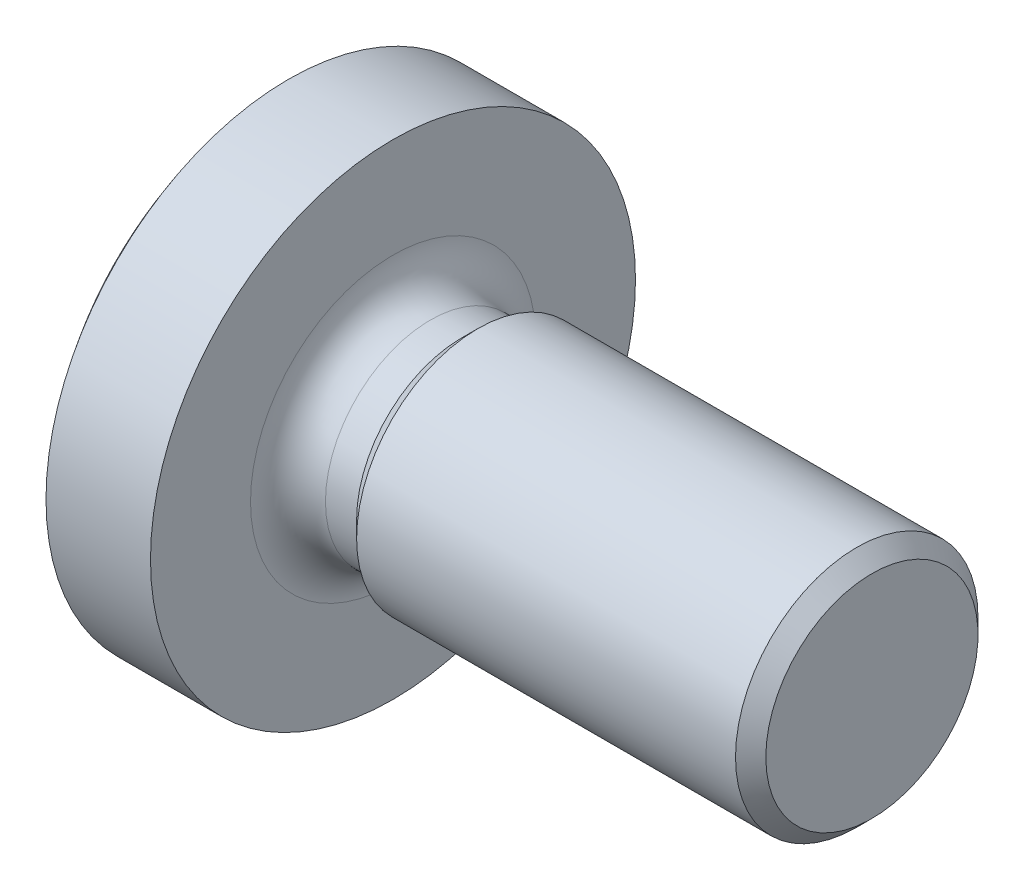
SolidWorks part; units mm, degrees
revolve "基体-旋转" add sketch "草图2" angle 360 about L0
sketch "草图2" plane through (0, 0, 0) normal (0, 0, 1) x (1, 0, 0)
  line L0 (-1.3318, 0) -> (6.5885, 0) construction
  line L1 (0, 0) -> (17.1, 0)
  line L2 (17.1, 0) -> (17.1, 2)
  line L3 (17.1, 2) -> (4.5, 2)
  line L4 (4.5, 2) -> (4.232, 1.732)
  line L5 (4.232, 1.732) -> (3.718, 1.732)
  line L6 (3.1, 2.35) -> (3.1, 4)
  line L7 (3.1, 4) -> (1.3765, 4)
  arc A0 (3.1, 2.35) -> (3.718, 1.732) centre (3.718, 2.35) ccw
  arc A1 (0, 0) -> (1.3765, 4) centre (6.5, 0) cw
  dimension "D3" = 6.5
  dimension "dk" = 8
  dimension "d" = 4
  dimension "l" = 14
  dimension "a" = 1.4
  dimension "D1" = 45
  dimension "D2" = 3.464
  dimension "da" = 4.7
  dimension "k" = 3.1
cosmetic thread "装饰螺纹线1" parameters "D1"=12.6, "D2"=3.464
material "钢"
ref_plane "前视" through (0, 0, 0) normal (0, 0, 1) x (1, 0, 0)
ref_plane "上视" through (0, 0, 0) normal (0, 1, 0) x (1, 0, 0)
ref_plane "右视" through (0, 0, 0) normal (1, 0, 0) x (0, 0, -1)
sketch "尺寸草图" plane through (0, 0, 0) normal (0, 0, 1) x (1, 0, 0)
  line L0 (0, 0) -> (14, 0)
  line L1 (0, 0) -> (0, 8)
  line L2 (14, 0) -> (14, 4.7)
  point P5 (0, 4)
  point P6 (13.3, 0)
  point P7 (1.4, 0)
  point P8 (3.1, 0)
  point P9 (7.5, 0)
  point P10 (4.4, 0)
  point P11 (11.6, 0)
  dimension "dk" = 8
  dimension "d" = 4
  dimension "l" = 14
  dimension "a" = 1.4
  dimension "da" = 4.7
  dimension "k" = 3.1
  dimension "P" = 0.7
  dimension "rf" = 6.5
  dimension "m" = 4.4
  dimension "h" = 2.4
sketch "草图3" plane through (0, 0, 0) normal (0, 0, 1) x (1, 0, 0)
  line L0 (16.7538, 2) -> (17.4538, 2)
  line L1 (17.4538, 2) -> (17.1, 1.3938)
  line L2 (17.1, 1.3938) -> (16.7538, 2)
  line L3 (17.1, 2) -> (4.5, 2) construction
  line L4 (17.1, -2) -> (17.1, 2) construction
  line L5 (-0.2428, 0) -> (7.1644, 0) construction
  line L6 (-1.3318, 0) -> (6.5885, 0) construction
  dimension "P" = 0.7
  dimension "D1" = 0.6062
  dimension "D2" = 60
revolve "切除-旋转1" cut sketch "草图3" angle 360 about L5
sketch "草图5" plane through (0, 0, 0) normal (1, 0, 0) x (0, 0, -1)
  line L1 (0.35, 2.2) -> (-0.35, 2.2)
  line L2 (0.35, 2.2) -> (0.35, -2.2)
  line L3 (0.35, -2.2) -> (-0.35, -2.2)
  line L4 (-0.35, 2.2) -> (-0.35, -2.2)
  point P4 (0.35, 0)
  point P5 (0, 2.2)
  dimension "m" = 4.4
  dimension "D1" = 0.7
ref_plane "基准面1" through (2.4, 0, 0) normal (1, 0, 0) x (0, 0, -1)
pattern_linear "阵列(线性)1" [suppressed] count 19 spacing 0.7 along (1, 0, 0)
sketch "草图6" plane through (2.4, 0, 0) normal (1, 0, 0) x (0, 0, -1)
  point P0 (0, 0)
loft "切除-放样1" cut profiles "草图6", "草图5"
ref_plane "基准面2" through (0, 0, 0) normal (0, -0.7071, 0.7071) x (1, 0, 0)
mirror "镜向1" about plane through (0, 0, 0) normal (0, -0.7071, 0.7071) of "切除-放样1"
sketch "草图7" plane through (0, 0, 0) normal (0, 1, 0) x (1, 0, 0)
  line L1 (11, 2.9903) -> (19.17, 2.9903)
  line L2 (11, 2.9903) -> (11, -2.2712)
  line L3 (11, -2.2712) -> (19.17, -2.2712)
  line L4 (19.17, 2.9903) -> (19.17, -2.2712)
  dimension "D1" = 11
extrude "切除-拉伸1" cut sketch "草图7" against normal mid plane 10
chamfer "倒角1" distance 0.25 angle 45 1 edges at (11, 0, 2)
equation "\"l@草图2\" = \"l@尺寸草图\""
equation "\"dk@草图2\" = \"dk@尺寸草图\""
equation "\"k@草图2\" = \"k@尺寸草图\""
equation "\"D2@草图2\" = \"d@尺寸草图\"*0.866"
equation "\"a@草图2\" = \"a@尺寸草图\""
equation "\"D3@草图2\" = \"rf@尺寸草图\""
equation "\"d@草图2\" = \"d@尺寸草图\""
equation "\"da@草图2\" = \"da@尺寸草图\""
equation "\"D2@装饰螺纹线1\" = \"d@尺寸草图\"*0.866"
equation "\"D1@装饰螺纹线1\" = \"l@尺寸草图\"-\"a@尺寸草图\""
equation "\"P@草图3\" = \"P@尺寸草图\""
equation "\"D1@草图3\" = \"P@尺寸草图\"*0.866"
equation "\"h@基准面1\" = \"h@尺寸草图\""
equation "\"D1@草图5\" = \"P@尺寸草图\""
equation "\"m@草图5\" = \"m@尺寸草图\""
equation "\"D3@阵列(线性)1\" = \"P@尺寸草图\""
equation "\"D1@阵列(线性)1\" = (\"l@尺寸草图\"-\"a@尺寸草图\")/\"P@尺寸草图\"+1"
